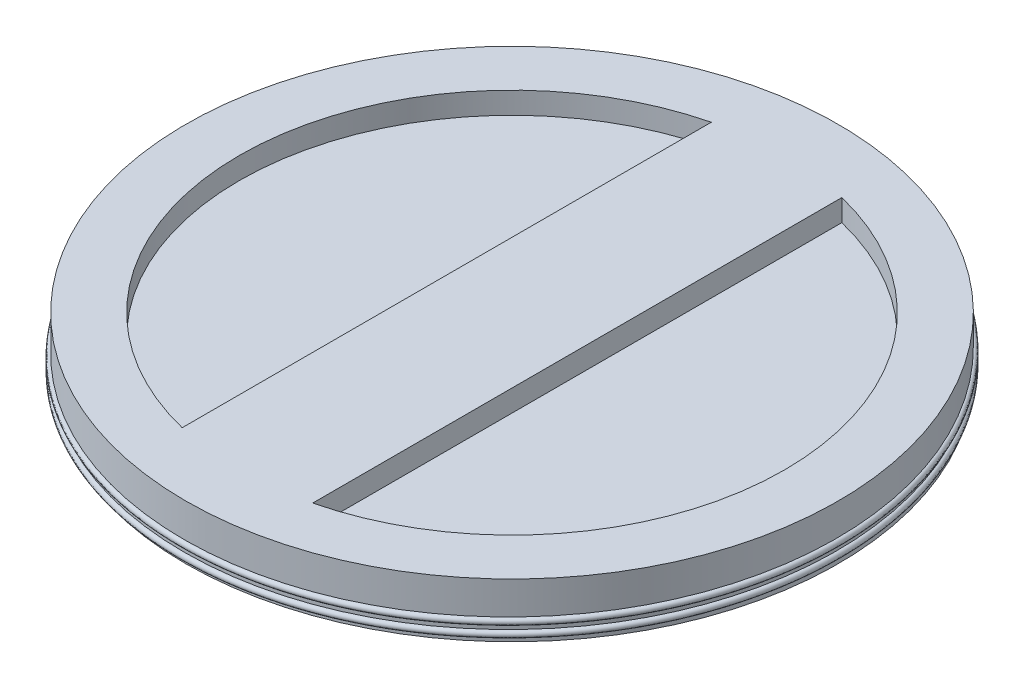
SolidWorks part; units mm, degrees
ref_plane "前视基准面" through (0, 0, 0) normal (0, 0, 1) x (1, 0, 0)
ref_plane "上视基准面" through (0, 0, 0) normal (0, 1, 0) x (1, 0, 0)
ref_plane "右视基准面" through (0, 0, 0) normal (1, 0, 0) x (0, 0, -1)
sketch "草图1" plane through (0, 0, 0) normal (0, 1, 0) x (1, 0, 0)
  circle A0 centre (0, 0) radius 30
  dimension "D1" = 60
extrude "凸台-拉伸1" add sketch "草图1" along normal blind 5
sketch "草图2" plane through (0, 5, 0) normal (0, 1, 0) x (1, 0, 0)
  line L0 (-6, 24.3284) -> (-6, -24.3284)
  line L1 (6, 24.3284) -> (6, -24.3284)
  arc A0 (-6, 24.3284) -> (-6, -24.3284) centre (0, 0) ccw
  arc A1 (6, -24.3284) -> (6, 24.3284) centre (0, 0) ccw
  dimension "D1" = 12
  dimension "D2" = 6
extrude "切除-拉伸1" cut sketch "草图2" against normal blind 2
sketch "草图4" plane through (0, 0, 0) normal (0, -1, 0) x (1, 0, 0)
  circle A0 centre (0, 0) radius 30
curve "螺旋线/涡状线1" pitch 1 height 2 turns 2
sketch "草图5" plane through (0, 0, 0) normal (0, 0, 1) x (1, 0, 0)
  line L0 (-30, 5) -> (-30, 0) construction
  circle A0 centre (-30, 0.3018) radius 0.3
  dimension "D1" = 0.6
sweep "扫描1" add profiles "草图5" path "螺旋线/涡状线1"
